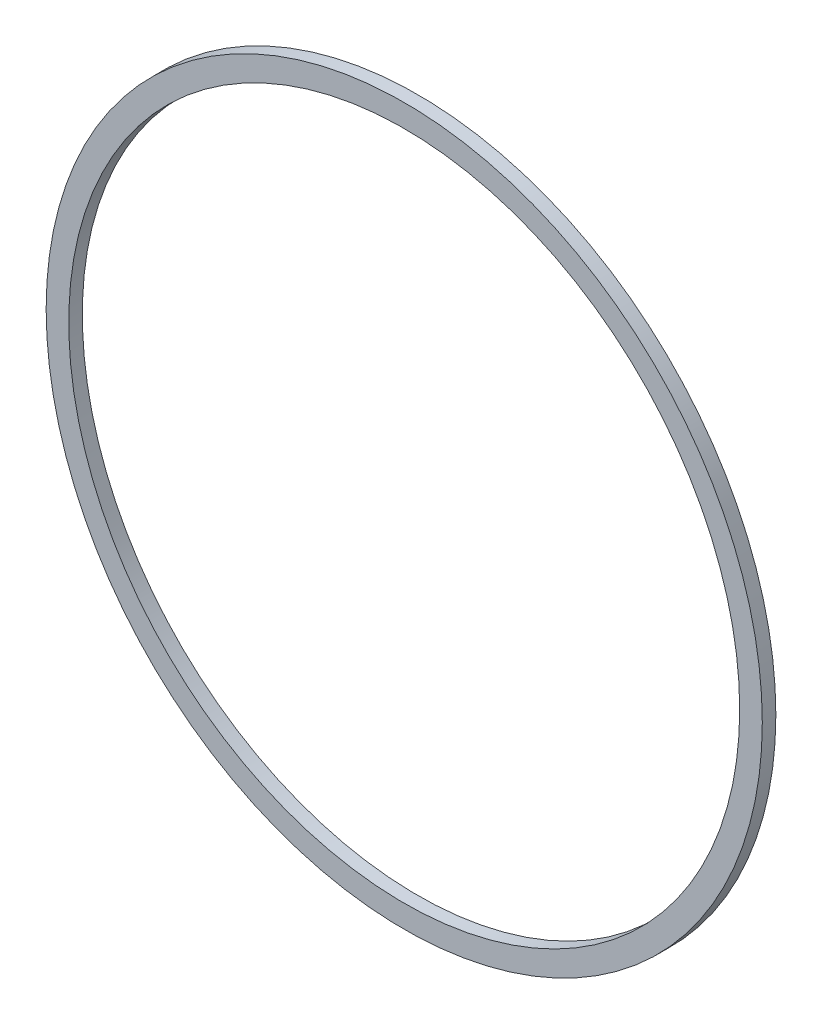
SolidWorks part; units mm, degrees
ref_plane "Ön Düzlem" through (0, 0, 0) normal (0, 0, 1) x (1, 0, 0)
ref_plane "Üst Düzlem" through (0, 0, 0) normal (0, 1, 0) x (1, 0, 0)
ref_plane "Sağ Düzlem" through (0, 0, 0) normal (1, 0, 0) x (0, 0, -1)
sketch "Çizim1" plane through (0, 0, 0) normal (0, 0, 1) x (1, 0, 0)
  circle A0 centre (0, 0) radius 14.85
  circle A1 centre (0, 0) radius 15.85
  dimension "D1" = 29.7
  dimension "D2" = 31.7
extrude "Yükseklik-Ekstrüzyon1" add sketch "Çizim1" along normal blind 0.6
